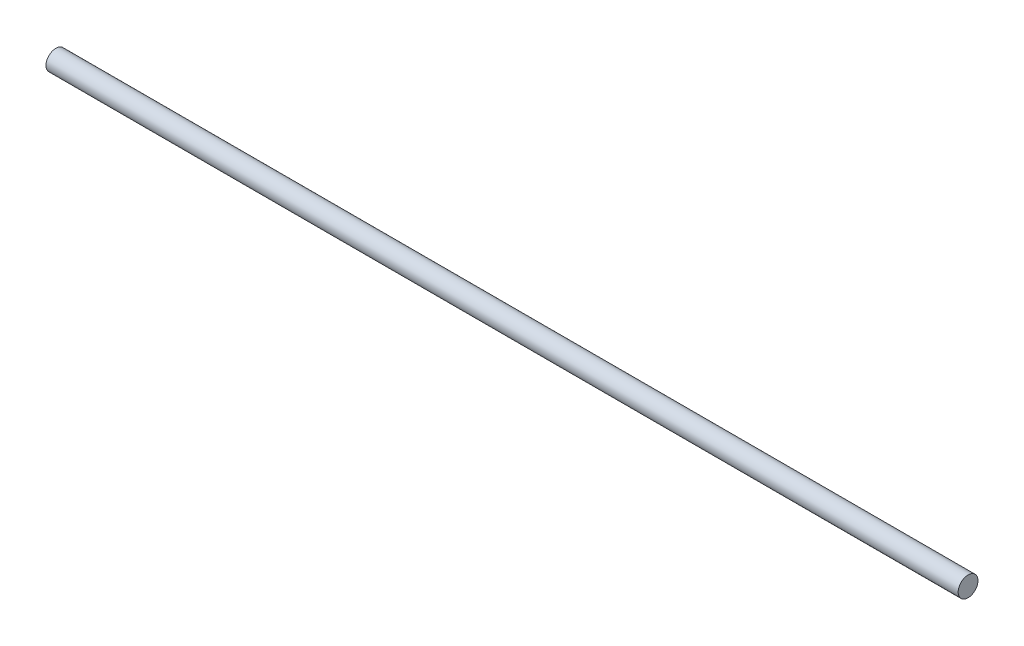
SolidWorks part; units mm, degrees
ref_plane "Front Plane" through (0, 0, 0) normal (0, 0, 1) x (1, 0, 0)
ref_plane "Top Plane" through (0, 0, 0) normal (0, 1, 0) x (1, 0, 0)
ref_plane "Right Plane" through (0, 0, 0) normal (1, 0, 0) x (0, 0, -1)
sketch "Sketch1" plane through (0, 0, 0) normal (1, 0, 0) x (0, 0, -1)
  circle A0 centre (0, 0) radius 1.25
  dimension "D1" = 2.5
extrude "Boss-Extrude1" add sketch "Sketch1" along normal blind 115
